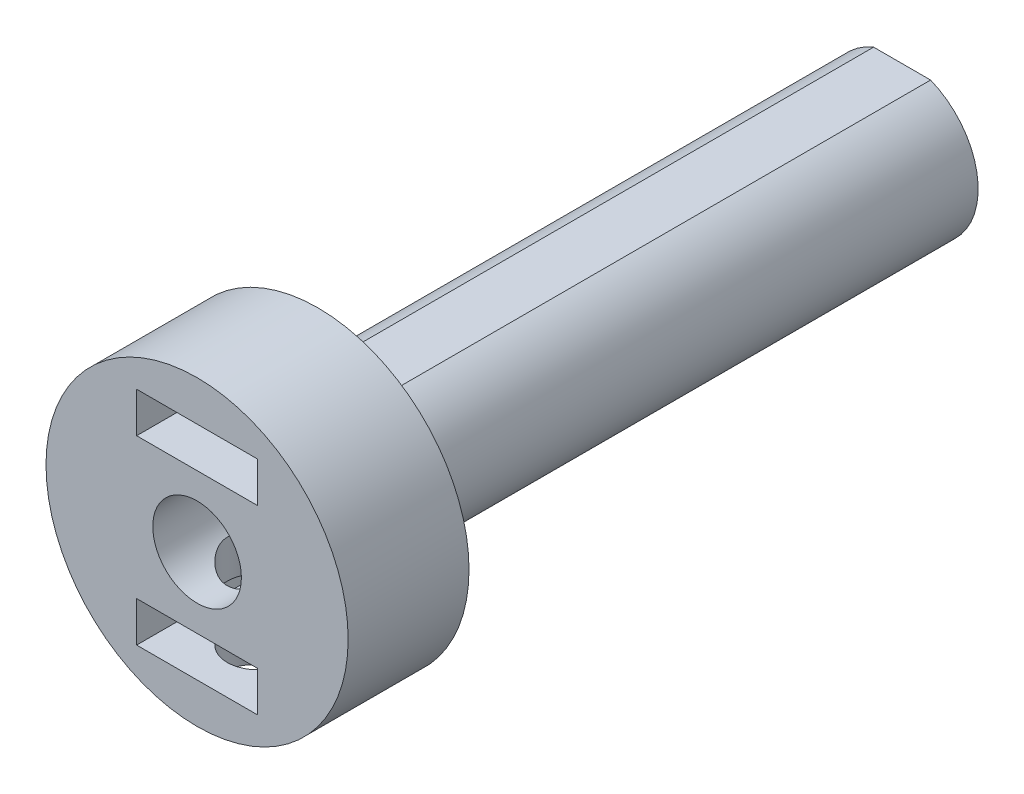
SolidWorks part; units mm, degrees
material "ABS"
ref_plane "Front Plane" through (0, 0, 0) normal (0, 0, 1) x (1, 0, 0)
ref_plane "Top Plane" through (0, 0, 0) normal (0, 1, 0) x (1, 0, 0)
ref_plane "Right Plane" through (0, 0, 0) normal (1, 0, 0) x (0, 0, -1)
sketch "Sketch1" plane through (0, 0, 0) normal (0, 0, 1) x (1, 0, 0)
  circle A0 centre (0, 0) radius 3.775
  circle A1 centre (0, 0) radius 2.2
  dimension "D1" = 7.55
  dimension "D2" = 4.4
extrude "Boss-Extrude1" add sketch "Sketch1" along normal blind 35
sketch "Sketch2" plane through (0, 0, 35) normal (0, 0, 1) x (1, 0, 0)
  circle A0 centre (0, 0) radius 3.775
  circle A1 centre (0, 0) radius 7.5
  dimension "D1" = 15
extrude "Boss-Extrude2" add sketch "Sketch2" against normal blind 6
sketch "Sketch3" plane through (0, 0, 35) normal (0, 0, 1) x (1, 0, 0)
  line L0 (0, 0) -> (0, 7.5) construction
  line L1 (-7.5, 0) -> (7.5, 0) construction
  line L2 (-3, 5.5) -> (3, 5.5)
  line L3 (-3, 5.5) -> (-3, 3.5)
  line L4 (-3, 3.5) -> (3, 3.5)
  line L5 (3, 5.5) -> (3, 3.5)
  line L6 (-3, 5.5) -> (3, 3.5) construction
  line L7 (-3, 3.5) -> (3, 5.5) construction
  line L8 (-3, -3.5) -> (3, -3.5)
  line L9 (3, -5.5) -> (3, -3.5)
  line L10 (-3, -5.5) -> (3, -5.5)
  line L11 (-3, -5.5) -> (-3, -3.5)
  circle A0 centre (0, 0) radius 7.5 construction
  point P6 (0, 4.5)
  dimension "D1" = 6
  dimension "D2" = 2
  dimension "D3" = 3.5
extrude "Cut-Extrude1" cut sketch "Sketch3" against normal through all
sketch "Sketch4" plane through (0, 0, 0) normal (0, 1, 0) x (1, 0, 0)
  line L0 (0, -35) -> (0, -29) construction
  line L1 (-7.5, -35) -> (7.5, -35) construction
  line L2 (7.5, -29) -> (-7.5, -29) construction
  circle A0 centre (0, -32) radius 1.5
  point P8 (0, 0)
  point P9 (0, -23.4838)
  point P10 (0, -32)
  dimension "D1" = 3
extrude "Cut-Extrude2" cut sketch "Sketch4" against normal through all
